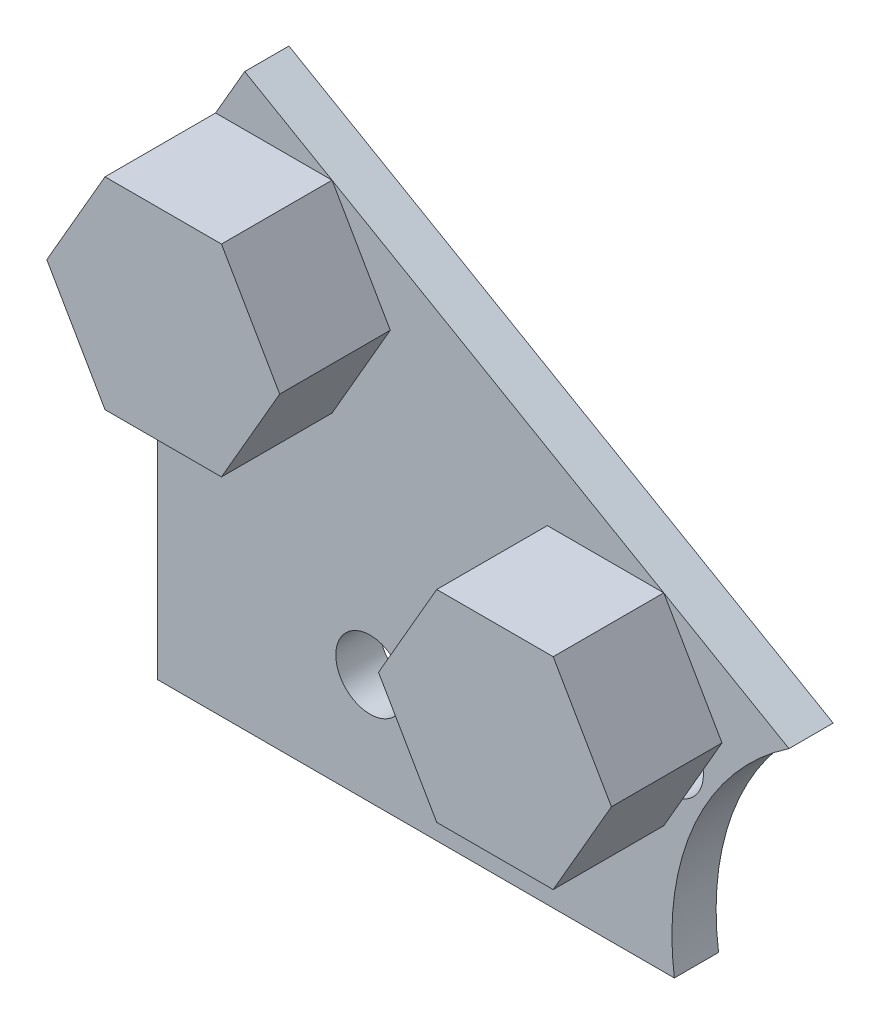
SolidWorks part; units mm, degrees
ref_plane "Plan de face" through (0, 0, 0) normal (0, 0, 1) x (1, 0, 0)
ref_plane "Plan de dessus" through (0, 0, 0) normal (0, 1, 0) x (1, 0, 0)
ref_plane "Plan de droite" through (0, 0, 0) normal (1, 0, 0) x (0, 0, -1)
sketch "Esquisse1" plane through (0, 0, 0) normal (0, 0, 1) x (1, 0, 0)
  line L1 (10, 0) -> (5, 8.6603) construction
  line L2 (5, 8.6603) -> (-5, 8.6603) construction
  line L3 (-5, 8.6603) -> (-10, 0) construction
  line L4 (-10, 0) -> (-5, -8.6603) construction
  line L5 (-5, -8.6603) -> (5, -8.6603) construction
  line L6 (5, -8.6603) -> (10, 0) construction
  line L7 (-10, 0) -> (-5, 8.6603) construction
  line L8 (-5, 8.6603) -> (-10, 17.3205) construction
  line L9 (-10, 17.3205) -> (-20, 17.3205) construction
  line L10 (-20, 17.3205) -> (-25, 8.6603) construction
  line L11 (-25, 8.6603) -> (-20, 0) construction
  line L12 (-20, 0) -> (-10, 0) construction
  line L13 (-25, 8.6603) -> (-20, 17.3205) construction
  line L14 (-20, 17.3205) -> (-25, 25.9808) construction
  line L15 (-25, 25.9808) -> (-35, 25.9808) construction
  line L16 (-35, 25.9808) -> (-40, 17.3205) construction
  line L17 (-40, 17.3205) -> (-35, 8.6603) construction
  line L18 (-35, 8.6603) -> (-25, 8.6603) construction
  line L19 (-9.7343, 8.6603) -> (-12.3671, 13.2205)
  line L20 (-12.3671, 13.2205) -> (-17.6329, 13.2205)
  line L21 (-17.6329, 13.2205) -> (-20.2657, 8.6603)
  line L22 (-20.2657, 8.6603) -> (-17.6329, 4.1)
  line L23 (-17.6329, 4.1) -> (-12.3671, 4.1)
  line L24 (-12.3671, 4.1) -> (-9.7343, 8.6603)
  line L25 (-32.6329, 21.8808) -> (-35.2657, 17.3205)
  line L26 (-35.2657, 17.3205) -> (-32.6329, 12.7603)
  line L27 (-32.6329, 12.7603) -> (-27.3671, 12.7603)
  line L28 (-27.3671, 12.7603) -> (-24.7343, 17.3205)
  line L29 (-24.7343, 17.3205) -> (-27.3671, 21.8808)
  line L30 (-27.3671, 21.8808) -> (-32.6329, 21.8808)
  circle A0 centre (0, 0) radius 8.6603 construction
  circle A1 centre (-15, 8.6603) radius 8.6603 construction
  circle A2 centre (-30, 17.3205) radius 8.6603 construction
  circle A3 centre (-15, 8.6603) radius 4.5603 construction
  circle A4 centre (-30, 17.3205) radius 4.5603 construction
  point P11 (0, 0)
  point P12 (0, 0)
  point P30 (0, 0)
  dimension "D1" = 10
  dimension "D2" = 4.1
extrude "Boss.-Extru.1" add sketch "Esquisse1" along normal blind 5
sketch "Esquisse2" plane through (0, 0, 0) normal (0, 0, 1) x (1, 0, 0)
  line L0 (0, 0) -> (-47.9544, 27.6865) construction
  line L1 (-31.3164, 24.1609) -> (-12.3671, 13.2205)
  line L2 (-12.3671, 13.2205) -> (-4.8671, 8.8904)
  line L3 (-4.8671, 8.8904) -> (-10.9373, -1.6235)
  line L4 (-35.2657, 17.3205) -> (-32.6329, 12.7603) construction
  line L6 (-31.3164, 24.1609) -> (-35.2657, 17.3205)
  line L7 (-5, 8.6603) -> (-10, 0) construction
  line L8 (-32.6329, 21.8808) -> (-35.2657, 17.3205) construction
  line L10 (-10.9373, -1.6235) -> (-35.2657, -1.6235)
  line L11 (-25.6473, 3.3765) -> (-29.2708, 16.8995) construction
  line L12 (-35.2657, 17.3205) -> (-35.2657, -1.6235)
  circle A0 centre (-12.1244, 7) radius 1.55
  circle A1 centre (-12.1244, 7) radius 14 construction
  circle A2 centre (-29.2708, 16.8995) radius 1.55
  circle A3 centre (-25.6473, 3.3765) radius 1.55
  point P10 (-36.5571, 0.0475)
  point P13 (-35.2443, 17.2834)
  point P28 (0, 0)
  dimension "D1" = 28
  dimension "D3" = 3.1
  dimension "D2" = 14
  dimension "D4" = 14
  dimension "D5" = 5
extrude "Boss.-Extru.2" add sketch "Esquisse2" against normal blind 2
sketch "Esquisse4" plane through (0, 0, 0) normal (0, 0, 1) x (1, 0, 0)
  circle A0 centre (0, 0) radius 12
  dimension "D1" = 24
extrude "Enlèv. mat.-Extru.2" cut sketch "Esquisse4" against normal through all
